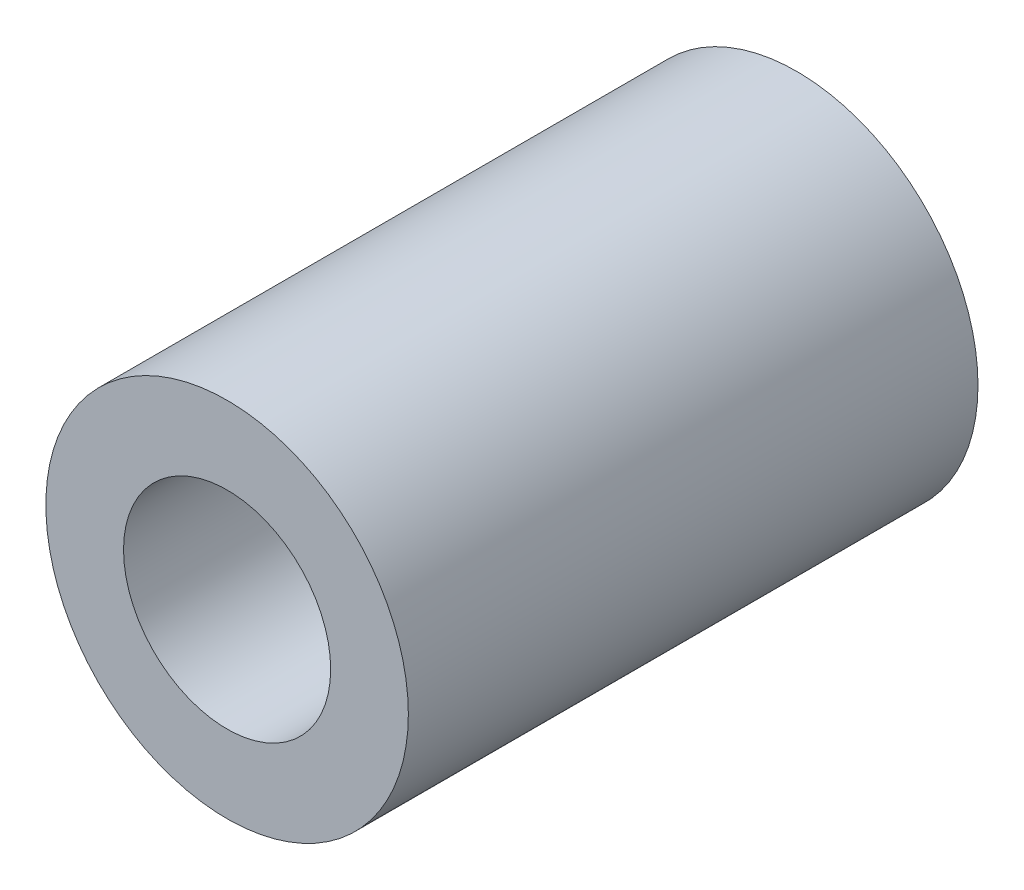
SolidWorks part; units mm, degrees
ref_plane "前视基准面" through (0, 0, 0) normal (0, 0, 1) x (1, 0, 0)
ref_plane "上视基准面" through (0, 0, 0) normal (0, 1, 0) x (1, 0, 0)
ref_plane "右视基准面" through (0, 0, 0) normal (1, 0, 0) x (0, 0, -1)
sketch "草图1" plane through (0, 0, 0) normal (0, 0, 1) x (1, 0, 0)
  circle A0 centre (0, 0) radius 7
  circle A1 centre (0, 0) radius 2.5
  dimension "D1" = 5
  dimension "D2" = 14
extrude "凸台-拉伸1" add sketch "草图1" along normal blind 22
sketch "草图2" plane through (0, 0, 22) normal (0, 0, 1) x (1, 0, 0)
  circle A0 centre (0, 0) radius 4
  dimension "D1" = 8
extrude "切除-拉伸1" cut sketch "草图2" against normal blind 11
